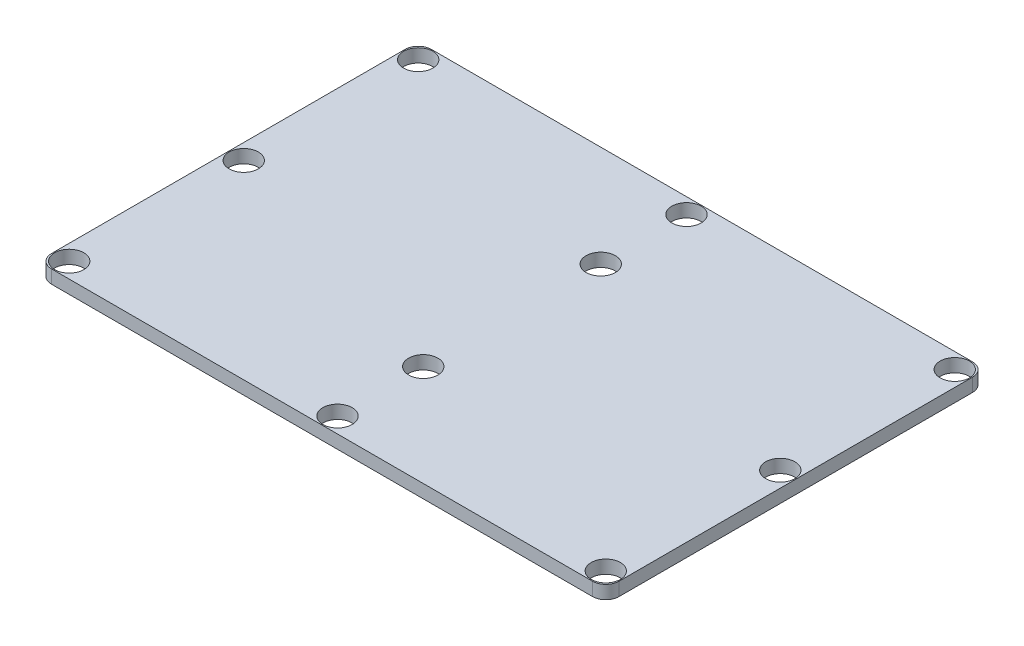
SolidWorks part; units mm, degrees
ref_plane "Front Plane" through (0, 0, 0) normal (0, 0, 1) x (1, 0, 0)
ref_plane "Top Plane" through (0, 0, 0) normal (0, 1, 0) x (1, 0, 0)
ref_plane "Right Plane" through (0, 0, 0) normal (1, 0, 0) x (0, 0, -1)
sketch "Sketch1" plane through (0, 0, 0) normal (0, 1, 0) x (1, 0, 0)
  line L1 (-64, -42.85) -> (64, -42.85)
  line L2 (-64, -42.85) -> (-64, 42.85)
  line L3 (-64, 42.85) -> (64, 42.85)
  line L4 (64, -42.85) -> (64, 42.85)
  line L5 (-64, -42.85) -> (64, 42.85) construction
  line L6 (-64, 42.85) -> (64, -42.85) construction
  point P0 (0, 0)
  dimension "D1" = 85.7
  dimension "D2" = 128
extrude "Boss-Extrude1" add sketch "Sketch1" along normal blind 3
hole_wizard "M6 Clearance Hole1" positions "Sketch2" profile "Sketch3" hole size "M6" standard "ANSI Metric" end condition through all
sketch "Sketch2" plane through (0, 3, 0) normal (0, 1, 0) x (1, 0, 0)
  line L0 (0, -1.65) -> (0, 1.65) construction
  line L1 (-1.65, 0) -> (1.65, 0) construction
  line L2 (64, 42.85) -> (-64, 42.85) construction
  line L3 (-64, 42.85) -> (-64, -42.85) construction
  line L4 (64, -42.85) -> (64, 42.85) construction
  line L5 (-64, -42.85) -> (64, -42.85) construction
  point P0 (-60.5, 39.35)
  point P2 (0, 39.35)
  point P6 (60.5, 39.35)
  point P8 (60.5, 0)
  point P12 (60.5, -39.35)
  point P14 (0, -39.35)
  point P16 (-60.5, -39.35)
  point P18 (-60.5, 0)
  point P20 (0, -20.01)
  point P22 (0, 20.01)
  dimension "D1" = 3.5
  dimension "D2" = 3.5
  dimension "D3" = 3.5
  dimension "D4" = 3.5
  dimension "D5" = 19.34
  dimension "D6" = 19.34
sketch "Sketch3" plane through (-60.5, 3, -39.35) normal (1, 0, 0) x (0, 0, 1)
  line L0 (0, 0) -> (0, 3)
  line L1 (0, 3) -> (3.3, 3)
  line L2 (3.3, 3) -> (3.3, 0)
  line L5 (3.3, 0) -> (0, 0)
  line L11 (0, -6.35) -> (0, 107.95) construction
  dimension "Thru Hole Dia." = 6.6
  dimension "Thru Hole Depth" = 3
fillet "Fillet1" radius 3 4 edges at (64, 1.5, -42.85) (64, 1.5, 42.85) (-64, 1.5, -42.85) (-64, 1.5, 42.85)
equation "\"D2@Sketch2\"=\"D1@Sketch2\""
equation "\"D3@Sketch2\"=\"D1@Sketch2\""
equation "\"D4@Sketch2\"=\"D1@Sketch2\""
equation "\"D6@Sketch2\"=\"D5@Sketch2\""
